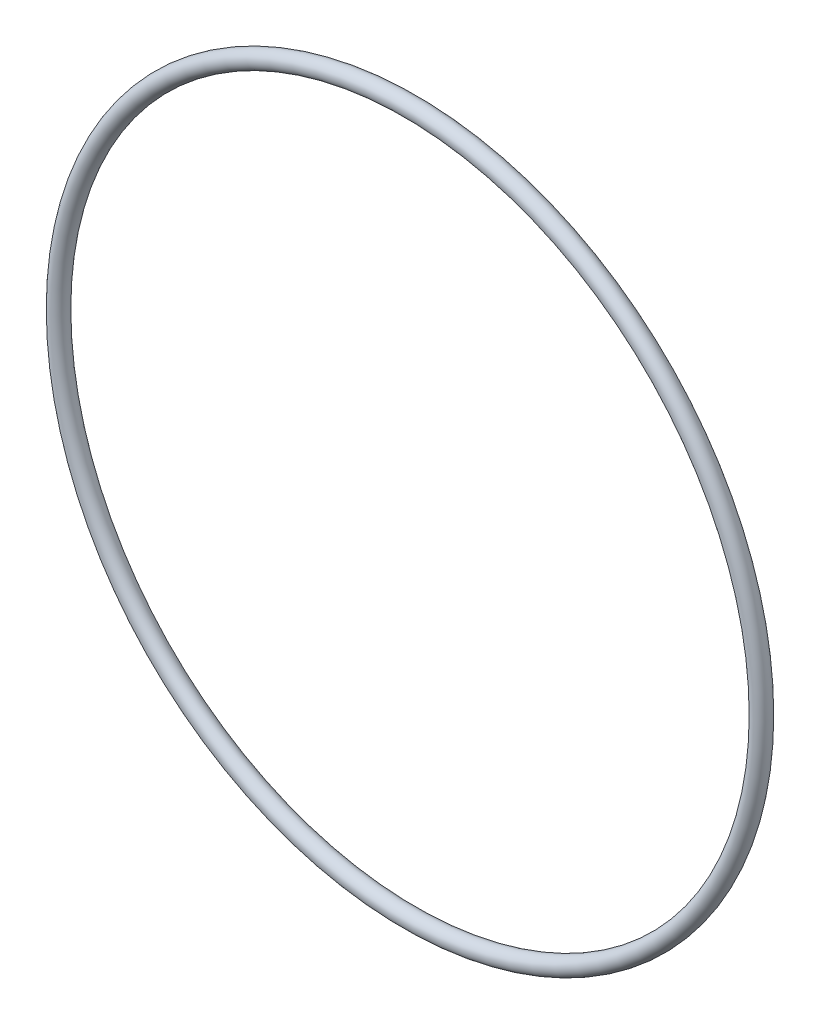
SolidWorks part; units mm, degrees
ref_plane "Front Plane" through (0, 0, 0) normal (0, 0, 1) x (1, 0, 0)
ref_plane "Top Plane" through (0, 0, 0) normal (0, 1, 0) x (1, 0, 0)
ref_plane "Right Plane" through (0, 0, 0) normal (1, 0, 0) x (0, 0, -1)
sketch "Sketch1" plane through (0, 0, 0) normal (0, 0, 1) x (1, 0, 0)
  line L0 (-73.1774, 0) -> (73.1774, 0) construction
  line L1 (-69.6468, 0) -> (69.6468, 0) construction
  line L2 (-51.7442, 51.7442) -> (51.7442, -51.7442) construction
  point P3 (69.6468, 0)
  point P4 (0, 0)
  point P8 (0, 0)
  point P9 (0, 0)
  point P10 (-73.1774, 0)
  point P11 (-69.6468, 0)
  point P14 (0, 0)
  point P15 (51.7442, -51.7442)
  point P16 (73.1774, 0)
  dimension "Actual OD" = 146.3548
  dimension "Actual ID" = 139.2936
  dimension "Actual Width" = 3.5306
  dimension "D1" = 45
sketch "Sketch2" plane through (0, 0, 0) normal (0, 1, 0) x (1, 0, 0)
  line L0 (-73.1774, 0) -> (73.1774, 0) construction
  line L1 (-71.4121, 1.7653) -> (-71.4121, -1.7653) construction
  line L2 (0, -1.7653) -> (0, 1.7653) construction
  circle A0 centre (-71.4121, 0) radius 1.7653
  point P12 (0, 0)
revolve "Revolve1" add sketch "Sketch2" angle 360 about L2
sketch "Sketch3" plane through (0, 0, 0) normal (1, 0, 0) x (0, 0, -1)
  line L0 (-1.7653, 0) -> (1.7653, 0) construction
  line L1 (-1.7653, -52.2351) -> (-1.7653, 52.2351) construction
  point P4 (0, 0)
  point P7 (-1.7653, 0)
  point P9 (-1.7653, -52.2351)
  dimension "D1" = 3.5306
  dimension "D2" = 104.4702
ref_plane "TopReference" through (0, 0, 1.7653) normal (0, 0, 1) x (1, 0, 0)
ref_plane "BottomReference" through (0, 0, -1.7653) normal (0, 0, 1) x (1, 0, 0)
equation "\"D1@Sketch3\"=\"Actual Width@Sketch1\""
equation "\"D2@Sketch3\"=\"Actual ID@Sketch1\"*.75"
